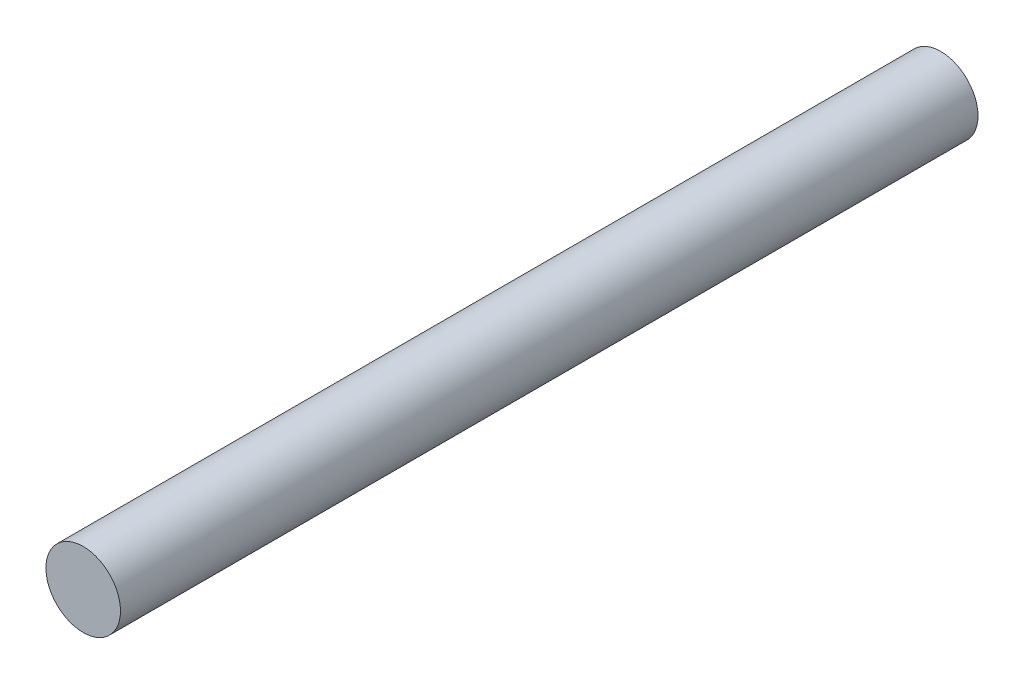
SolidWorks part; units mm, degrees
ref_plane "Front Plane" through (0, 0, 0) normal (0, 0, 1) x (1, 0, 0)
ref_plane "Top Plane" through (0, 0, 0) normal (0, 1, 0) x (1, 0, 0)
ref_plane "Right Plane" through (0, 0, 0) normal (1, 0, 0) x (0, 0, -1)
sketch "Sketch1" plane through (0, 0, 0) normal (0, 0, 1) x (1, 0, 0)
  circle A0 centre (0, 0) radius 5
  dimension "D1" = 10
extrude "Boss-Extrude1" add sketch "Sketch1" along normal blind 115
